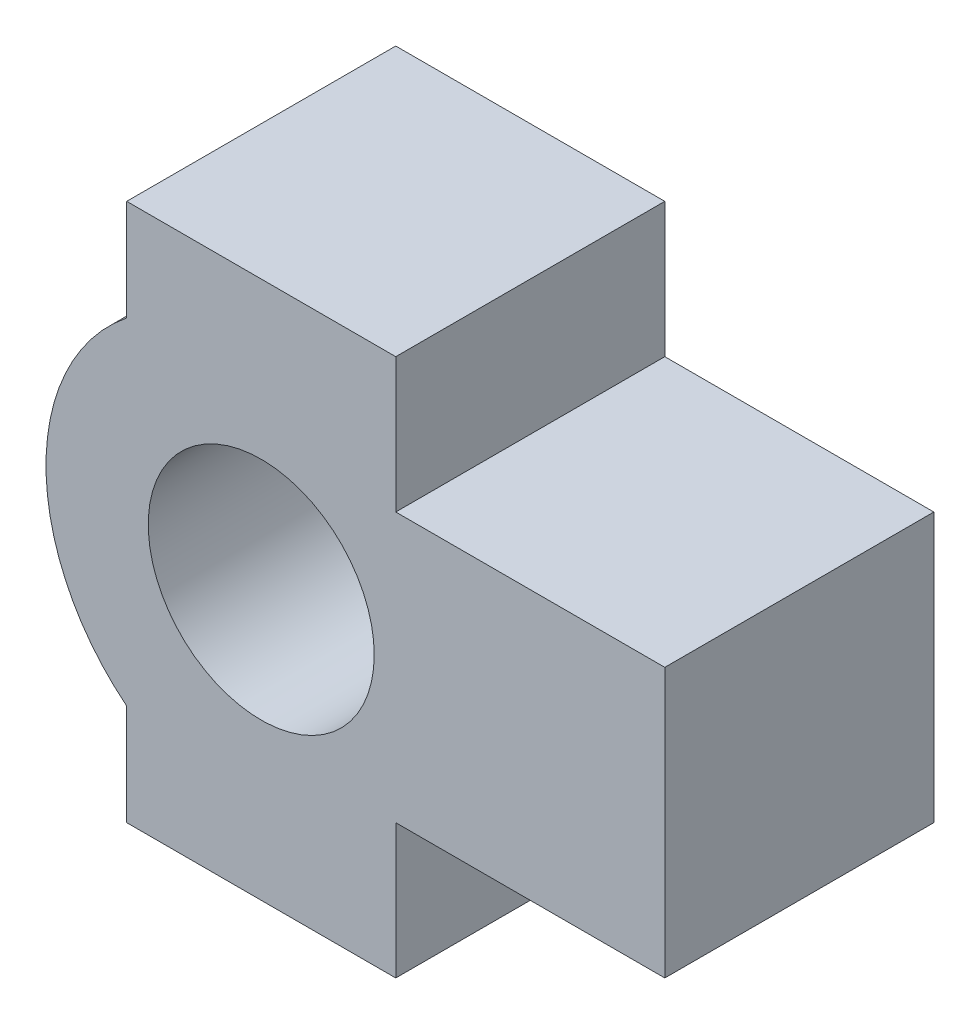
SolidWorks part; units mm, degrees
ref_plane "Front Plane" through (0, 0, 0) normal (0, 0, 1) x (1, 0, 0)
ref_plane "Top Plane" through (0, 0, 0) normal (0, 1, 0) x (1, 0, 0)
ref_plane "Right Plane" through (0, 0, 0) normal (1, 0, 0) x (0, 0, -1)
sketch "Sketch1" plane through (0, 0, 0) normal (0, 0, 1) x (1, 0, 0)
  line L0 (-16.5541, 7.0946) -> (-21.5541, 7.0946)
  line L1 (-21.5541, 7.0946) -> (-21.5541, -2.9054)
  line L2 (-21.5541, -2.9054) -> (-16.5541, -2.9054)
  line L3 (-16.5541, -2.9054) -> (-16.5541, -0.4054)
  line L4 (-16.5541, -0.4054) -> (-11.5541, -0.4054)
  line L5 (-11.5541, -0.4054) -> (-11.5541, 4.5946)
  line L6 (-11.5541, 4.5946) -> (-16.5541, 4.5946)
  line L7 (-16.5541, 4.5946) -> (-16.5541, 7.0946)
  dimension "D1" = 5
  dimension "D2" = 10
  dimension "D3" = 5
  dimension "D4" = 5
  dimension "D5" = 2.5
extrude "Boss-Extrude1" add sketch "Sketch1" along normal blind 5
sketch "Sketch2" plane through (0, 0, 5) normal (0, 0, 1) x (1, 0, 0)
  line L0 (-21.5541, 7.0946) -> (-21.5541, -2.9054) construction
  line L1 (-16.5541, 7.0946) -> (-21.5541, 7.0946) construction
  circle A0 centre (-19.0541, 2.0946) radius 2.1
  dimension "D1" = 4.2
  dimension "D2" = 2.5
  dimension "D3" = 5
extrude "Cut-Extrude1" cut sketch "Sketch2" against normal blind 10
sketch "Sketch3" plane through (0, 0, 5) normal (0, 0, 1) x (1, 0, 0)
  line L0 (-21.5541, 7.0946) -> (-21.5541, -2.9054) construction
  line L1 (-21.5541, 5.2171) -> (-21.5541, -1.0279)
  arc A0 (-21.5541, 5.2171) -> (-21.5541, -1.0279) centre (-19.0541, 2.0946) ccw
extrude "Boss-Extrude2" add sketch "Sketch3" against normal blind 5
